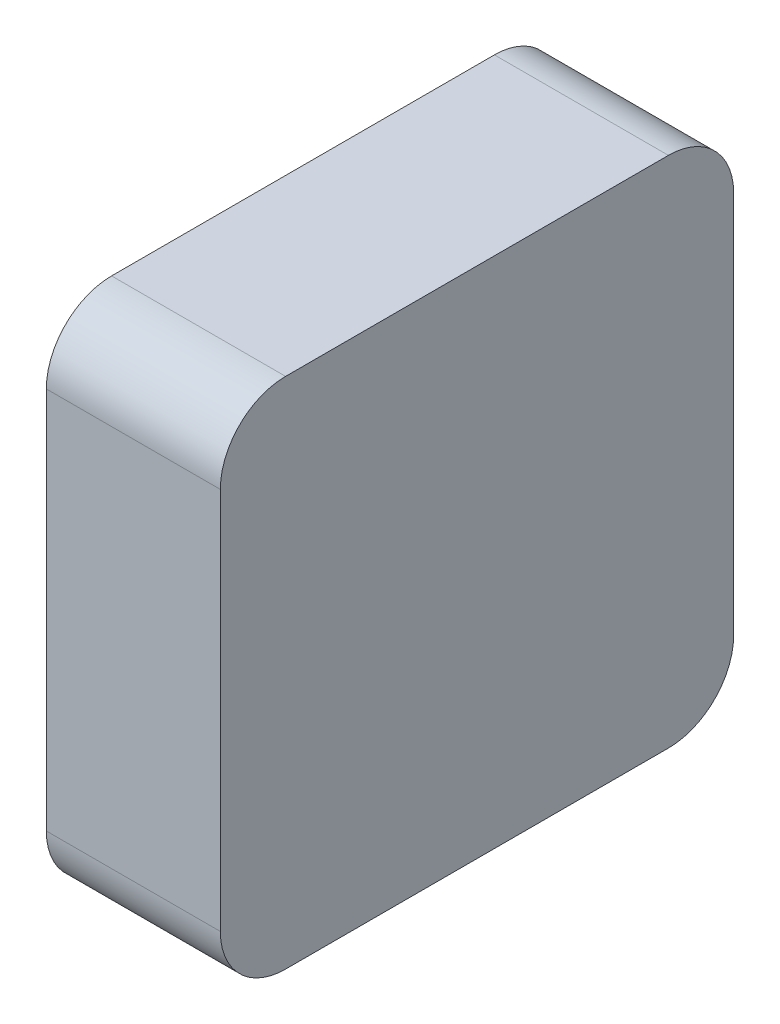
SolidWorks part; units mm, degrees
material "PPE"
ref_plane "Front Plane" through (0, 0, 0) normal (1, 0, 0) x (0, 1, 0)
ref_plane "Top Plane" through (0, 0, 0) normal (0, 0, 1) x (0, 1, 0)
ref_plane "Right Plane" through (0, 0, 0) normal (0, 1, 0) x (-1, 0, 0)
sketch "Sketch1" plane through (0, 0, 0) normal (1, 0, 0) x (0, 1, 0)
  line L1 (-11.176, -14.986) -> (11.176, -14.986)
  line L2 (-14.986, -11.176) -> (-14.986, 11.176)
  line L3 (-11.176, 14.986) -> (11.176, 14.986)
  line L4 (14.986, -11.176) -> (14.986, 11.176)
  line L5 (-14.986, -14.986) -> (14.986, 14.986) construction
  line L6 (-14.986, 14.986) -> (14.986, -14.986) construction
  arc A0 (-11.176, -14.986) -> (-14.986, -11.176) centre (-11.176, -11.176) cw
  arc A1 (-14.986, 11.176) -> (-11.176, 14.986) centre (-11.176, 11.176) cw
  arc A2 (11.176, -14.986) -> (14.986, -11.176) centre (11.176, -11.176) ccw
  arc A3 (11.176, 14.986) -> (14.986, 11.176) centre (11.176, 11.176) cw
  point P0 (0, 0)
  dimension "D2" = 3.81
  dimension "D1" = 29.972
extrude "Boss-Extrude1" add sketch "Sketch1" along normal blind 10.16
